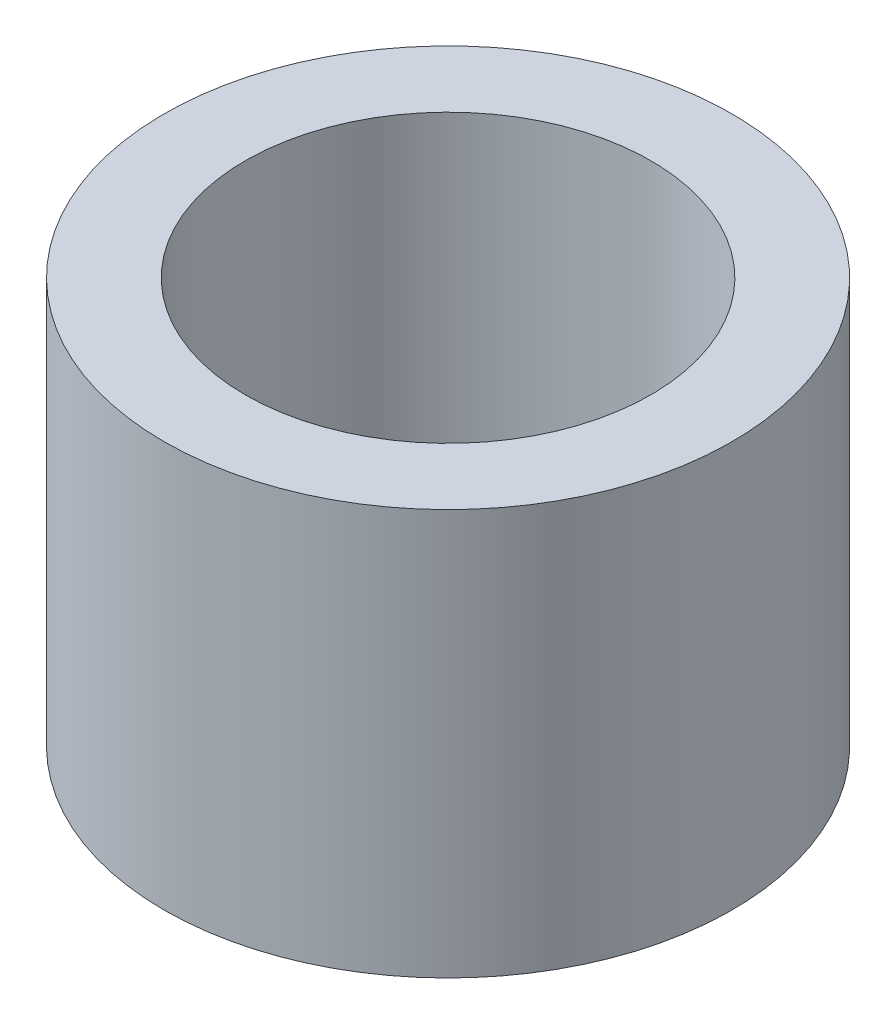
SolidWorks part; units mm, degrees
ref_plane "Front" through (0, 0, 0) normal (0, 0, 1) x (1, 0, 0)
ref_plane "Top" through (0, 0, 0) normal (0, 1, 0) x (1, 0, 0)
ref_plane "Right" through (0, 0, 0) normal (1, 0, 0) x (0, 0, -1)
sketch "Sketch1" plane through (0, 0, 0) normal (0, 1, 0) x (1, 0, 0)
  circle A0 centre (0, 0) radius 2.5
  circle A1 centre (0, 0) radius 3.5
extrude "Boss-Extrude1" add sketch "Sketch1" along normal blind 5
